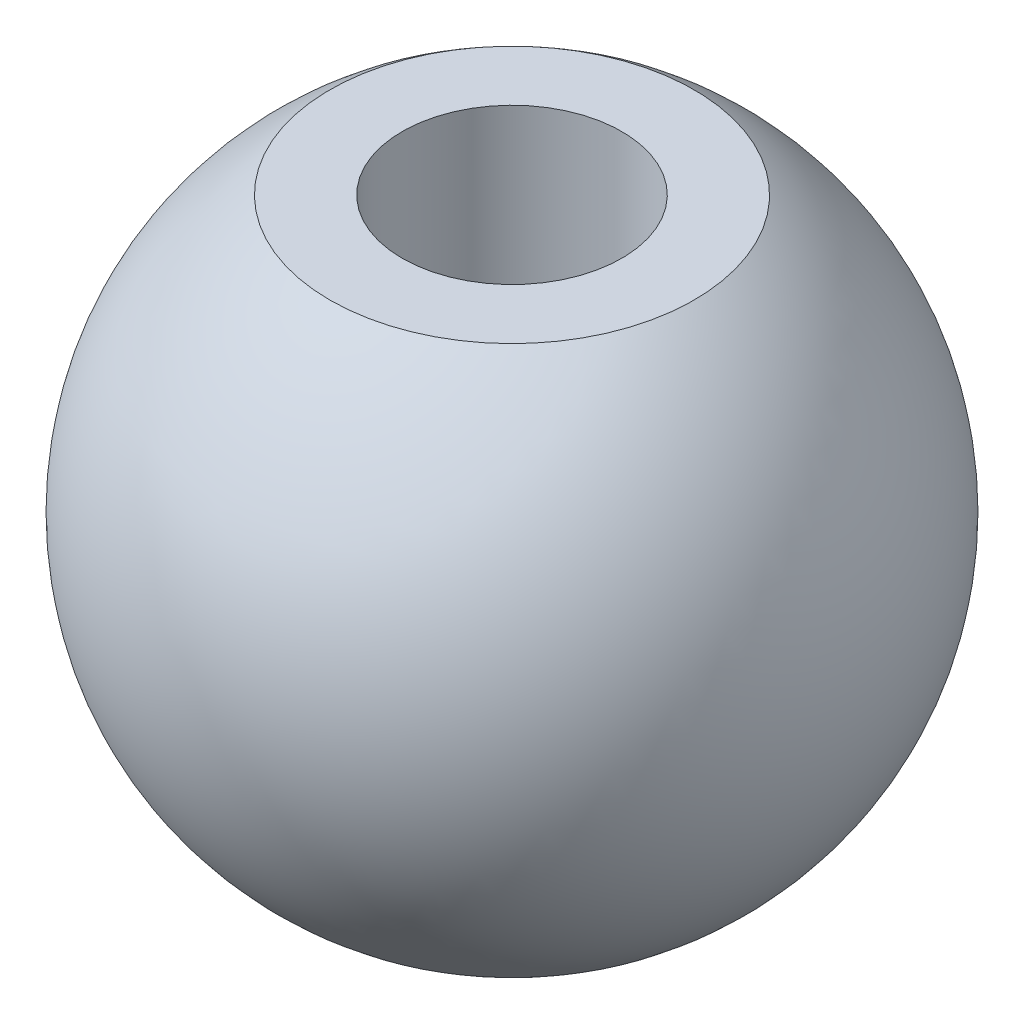
SolidWorks part; units mm, degrees
ref_plane "前视基准面" through (0, 0, 0) normal (0, 0, 1) x (1, 0, 0)
ref_plane "上视基准面" through (0, 0, 0) normal (0, 1, 0) x (1, 0, 0)
ref_plane "右视基准面" through (0, 0, 0) normal (1, 0, 0) x (0, 0, -1)
other "Configuration Table"
sketch "草图1" plane through (0, 0, 0) normal (0, 1, 0) x (1, 0, 0)
  line L0 (0, 3) -> (0, -3)
  arc A2 (0, 3) -> (0, -3) centre (0, 0) ccw
  dimension "D1" = 6
revolve "旋转4" add sketch "草图1" angle 360 about L0
ref_plane "基准面1" through (0, 2.5, 0) normal (0, 1, 0) x (1, 0, 0)
sketch "草图2" plane through (0, 2.5, 0) normal (0, 1, 0) x (1, 0, 0)
  circle A0 centre (0, 0) radius 2
  dimension "D1" = 4
extrude "切除-拉伸1" cut sketch "草图2" along normal blind 10
sketch "草图3" plane through (0, 2.5, 0) normal (0, 1, 0) x (1, 0, 0)
  circle A0 centre (0, 0) radius 1
  dimension "D1" = 2
extrude "切除-拉伸2" cut sketch "草图3" against normal blind 10
mirror "镜向1" about plane through (0, 0, 0) normal (0, 1, 0) of "切除-拉伸1"
